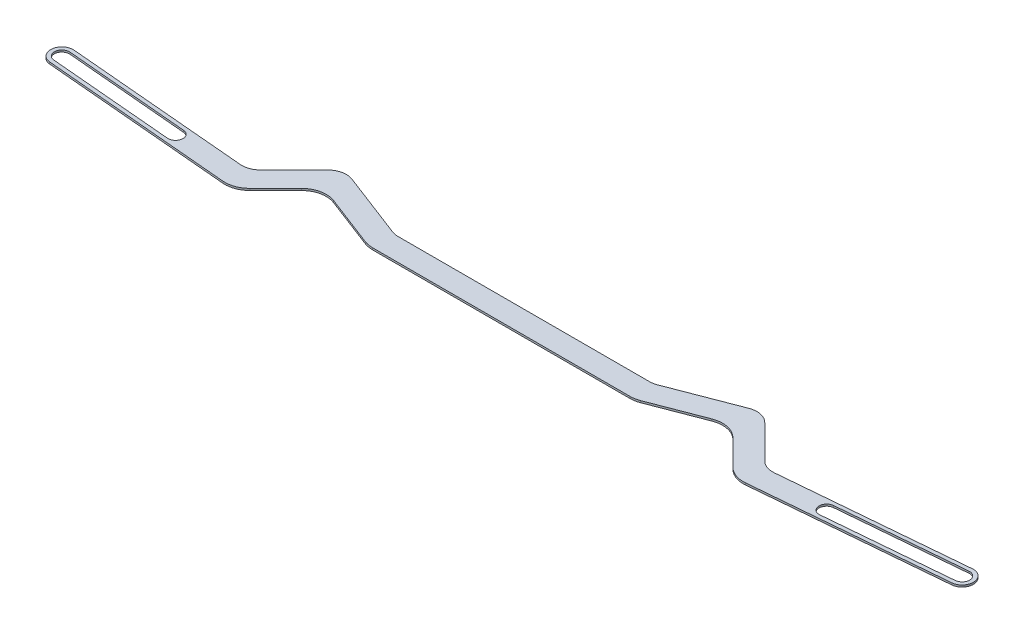
SolidWorks part; units mm, degrees
ref_plane "Front Plane" through (0, 0, 0) normal (0, 0, 1) x (1, 0, 0)
ref_plane "Top Plane" through (0, 0, 0) normal (0, 1, 0) x (1, 0, 0)
ref_plane "Right Plane" through (0, 0, 0) normal (1, 0, 0) x (0, 0, -1)
sketch "Sketch1" plane through (0, 0, 0) normal (0, 1, 0) x (1, 0, 0)
  line L0 (0, 0) -> (105, 0) construction
  line L1 (105, 0) -> (165.6827, 23.2939) construction
  line L2 (165.6827, 23.2939) -> (203.1594, -14.1827) construction
  line L3 (203.1594, -14.1827) -> (360, -0.461) construction
  line L4 (206.5558, -4.8512) -> (359.2156, 8.5048) construction
  line L5 (105.9274, 9.9963) -> (158.8198, 30.2998)
  line L6 (174.8019, 26.9027) -> (201.6098, 0.0947)
  line L7 (213.5238, -4.2416) -> (359.2156, 8.5048)
  line L8 (0, -9) -> (102.9613, -9)
  line L9 (110.1286, -7.6716) -> (151.3261, 8.1426)
  line L10 (172.6356, 3.6131) -> (193.1684, -16.9197)
  line L11 (209.0537, -22.7014) -> (360.7844, -9.4267)
  line L12 (0, 9) -> (0, -9)
  line L28 (0, 9) -> (100.5519, 9)
  line L30 (0, 9) -> (103.3319, 9) construction
  line L94 (167.9139, 33.7907) -> (206.5558, -4.8512) construction
  line L95 (103.3319, 9) -> (167.9139, 33.7907) construction
  line L165 (0, -9) -> (106.6681, -9) construction
  line L166 (106.6681, -9) -> (163.4516, 12.7972) construction
  line L167 (163.4516, 12.7972) -> (199.763, -23.5143) construction
  line L168 (199.763, -23.5143) -> (360.7844, -9.4267) construction
  arc A0 (359.2156, 8.5048) -> (360.7844, -9.4267) centre (360, -0.461) cw
  arc A1 (100.5519, 9) -> (105.9274, 9.9963) centre (100.5519, 24) ccw
  arc A2 (201.6098, 0.0947) -> (213.5238, -4.2416) centre (212.2164, 10.7013) ccw
  arc A3 (158.8198, 30.2998) -> (174.8019, 26.9027) centre (164.1953, 16.2961) cw
  arc A14 (102.9613, -9) -> (110.1286, -7.6716) centre (102.9613, 11) ccw
  arc A15 (193.1684, -16.9197) -> (209.0537, -22.7014) centre (207.3105, -2.7775) ccw
  arc A16 (172.6356, 3.6131) -> (151.3261, 8.1426) centre (158.4934, -10.529) ccw
  point P3 (-177.65, 222.9631)
  point P205 (106.6681, -9)
  point P209 (199.763, -23.5143)
  dimension "D18" = 20
  dimension "D10" = 15
  dimension "D1" = 105
  dimension "D2" = 65
  dimension "D3" = 53
  dimension "D4" = 360
  dimension "D5" = 175
  dimension "D6" = 159
  dimension "D7" = 45
  dimension "D8" = 9
  dimension "D9" = 9
extrude "Boss-Extrude1" add sketch "Sketch1" along normal blind 1.5
sketch "Sketch2" plane through (0, 1.5, 0) normal (0, 1, 0) x (1, 0, 0)
  line L0 (221.6623, -3.5296) -> (223.2474, -21.4596) construction
  line L1 (359.2156, 8.5048) -> (213.5238, -4.2416) construction
  line L2 (209.0537, -22.7014) -> (360.7844, -9.4267) construction
  line L3 (223.2474, -21.4596) -> (222.4549, -12.4946) construction
  line L4 (260.3805, -9.1765) -> (360, -0.461) construction
  line L5 (222.4549, -12.4946) -> (368.9658, 0.3234) construction
  line L6 (259.8576, -3.1994) -> (359.4771, 5.5162)
  line L7 (260.9035, -15.1537) -> (360.5229, -6.4381)
  arc A1 (360.7844, -9.4267) -> (359.2156, 8.5048) centre (360, -0.461) ccw construction
  arc A2 (259.8576, -3.1994) -> (260.9035, -15.1537) centre (260.3805, -9.1765) ccw
  arc A3 (360.5229, -6.4381) -> (359.4771, 5.5162) centre (360, -0.461) ccw
  point P9 (310.1903, -4.8188)
  dimension "D1" = 9
  dimension "D2" = 6
  dimension "D3" = 100
extrude "Cut-Extrude1" cut sketch "Sketch2" against normal through all
mirror "Mirror2" about plane through (0, 0, 0) normal (1, 0, 0) of bodies 102
